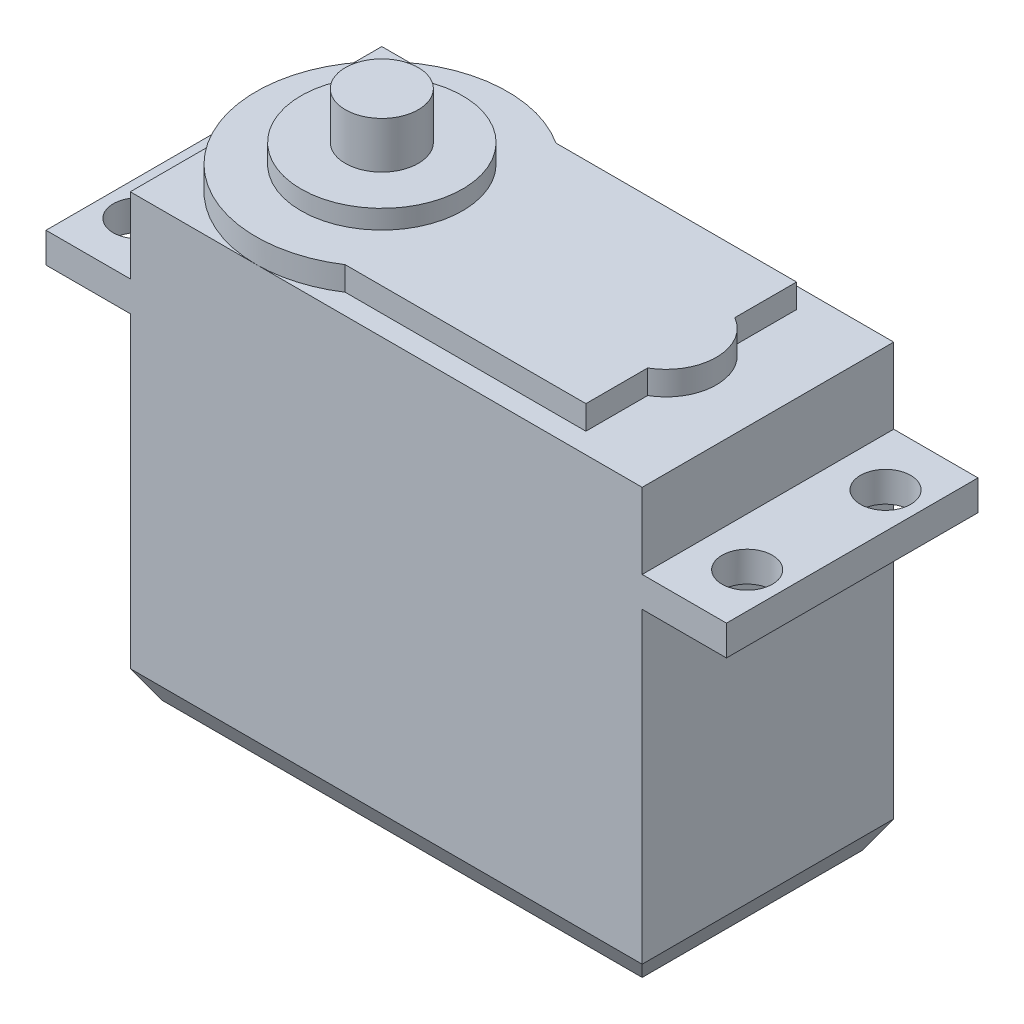
SolidWorks part; units mm, degrees
ref_plane "Plan de face" through (0, 0, 0) normal (0, 0, 1) x (1, 0, 0)
ref_plane "Plan de dessus" through (0, 0, 0) normal (0, 1, 0) x (1, 0, 0)
ref_plane "Plan de droite" through (0, 0, 0) normal (1, 0, 0) x (0, 0, -1)
sketch "Esquisse1" plane through (0, 0, 0) normal (0, 0, 1) x (1, 0, 0)
  line L1 (-20.35, -17.5) -> (20.35, -17.5)
  line L2 (-20.35, -17.5) -> (-20.35, 17.5)
  line L3 (-20.35, 17.5) -> (20.35, 17.5)
  line L4 (20.35, -17.5) -> (20.35, 17.5)
  line L5 (-20.35, -17.5) -> (20.35, 17.5) construction
  line L6 (-20.35, 17.5) -> (20.35, -17.5) construction
  point P0 (0, 0)
  dimension "D1" = 40.7
  dimension "D2" = 35
extrude "Extrusion1" add sketch "Esquisse1" along normal mid plane 20
sketch "Esquisse2" plane through (-20.35, 0, 0) normal (-1, 0, 0) x (0, 0, 1)
  line L0 (-10, 17.5) -> (-10, -17.5) construction
  line L1 (-10, 11.5) -> (10, 11.5)
  line L2 (-10, 11.5) -> (-10, 9.1)
  line L3 (-10, 9.1) -> (10, 9.1)
  line L4 (10, 11.5) -> (10, 9.1)
  line L5 (10, 17.5) -> (10, -17.5) construction
  line L6 (10, 17.5) -> (-10, 17.5) construction
  dimension "D1" = 6
  dimension "D2" = 2.4
extrude "Extrusion2" add sketch "Esquisse2" along normal blind 6.7
mirror "Symétrie1" about plane through (0, 0, 0) normal (1, 0, 0) of "Extrusion2"
chamfer "Chanfrein1" distance 1.25 angle 60 4 edges at (-20.35, -17.5, 0) (0, -17.5, -10) (20.35, -17.5, 0) (0, -17.5, 10)
sketch "Esquisse3" plane through (0, 17.5, 0) normal (0, 1, 0) x (1, 0, 0)
  line L0 (20.35, 10) -> (-20.35, 10) construction
  line L1 (20.35, -10) -> (-20.35, -10) construction
  line L3 (-20.35, -10) -> (-20.35, 10) construction
  line L4 (20.35, -10) -> (20.35, 10) construction
  line L5 (-4.8856, -8.375) -> (14.25, -8.375)
  line L6 (14.25, 3.4641) -> (14.25, 8.375)
  line L7 (-4.8856, 8.375) -> (14.25, 8.375)
  line L8 (14.25, -8.375) -> (14.25, -3.4641)
  line L9 (0, 0) -> (14.25, 8.375) construction
  line L10 (0, 0) -> (14.25, -8.375) construction
  arc A0 (-4.8856, 8.375) -> (-4.8856, -8.375) centre (-10.35, 0) ccw
  arc A1 (14.25, -3.4641) -> (14.25, 3.4641) centre (12.25, 0) ccw
  point P6 (0, 0)
  dimension "D3" = 8
  dimension "D1" = 16.75
  dimension "D2" = 6.1
  dimension "D4" = 2
extrude "Extrusion3" add sketch "Esquisse3" along normal blind 1.9
sketch "Esquisse4" plane through (0, 19.4, 0) normal (0, 1, 0) x (1, 0, 0)
  circle A0 centre (-10.35, 0) radius 6.425
  arc A1 (-4.8856, 8.375) -> (-4.8856, -8.375) centre (-10.35, 0) ccw construction
  dimension "D1" = 12.85
extrude "Extrusion4" add sketch "Esquisse4" along normal blind 1.5
sketch "Esquisse5" plane through (0, 11.5, 0) normal (0, 1, 0) x (1, 0, 0)
  line L0 (27.05, -10) -> (20.35, -10) construction
  line L1 (27.05, -10) -> (27.05, 10) construction
  circle A0 centre (24.2, -5.5) radius 2
  point P2 (23.7, -10)
  dimension "D1" = 4
  dimension "D2" = 4.5
  dimension "D3" = 2.85
extrude "Extrusion5" cut sketch "Esquisse5" against normal blind 10
pattern_linear "Répétition linéaire1" count 2 spacing 48.4 along (-1, 0, 0) of "Extrusion5"
mirror "Symétrie2" about plane through (0, 0, 0) normal (0, 0, 1) of "Répétition linéaire1", "Extrusion5"
sketch "Esquisse6" plane through (0, 20.9, 0) normal (0, 1, 0) x (1, 0, 0)
  circle A0 centre (-10.35, 0) radius 2.9
  circle A1 centre (-10.35, 0) radius 6.425 construction
  dimension "D1" = 5.8
extrude "Extrusion6" add sketch "Esquisse6" along normal blind 3.7
